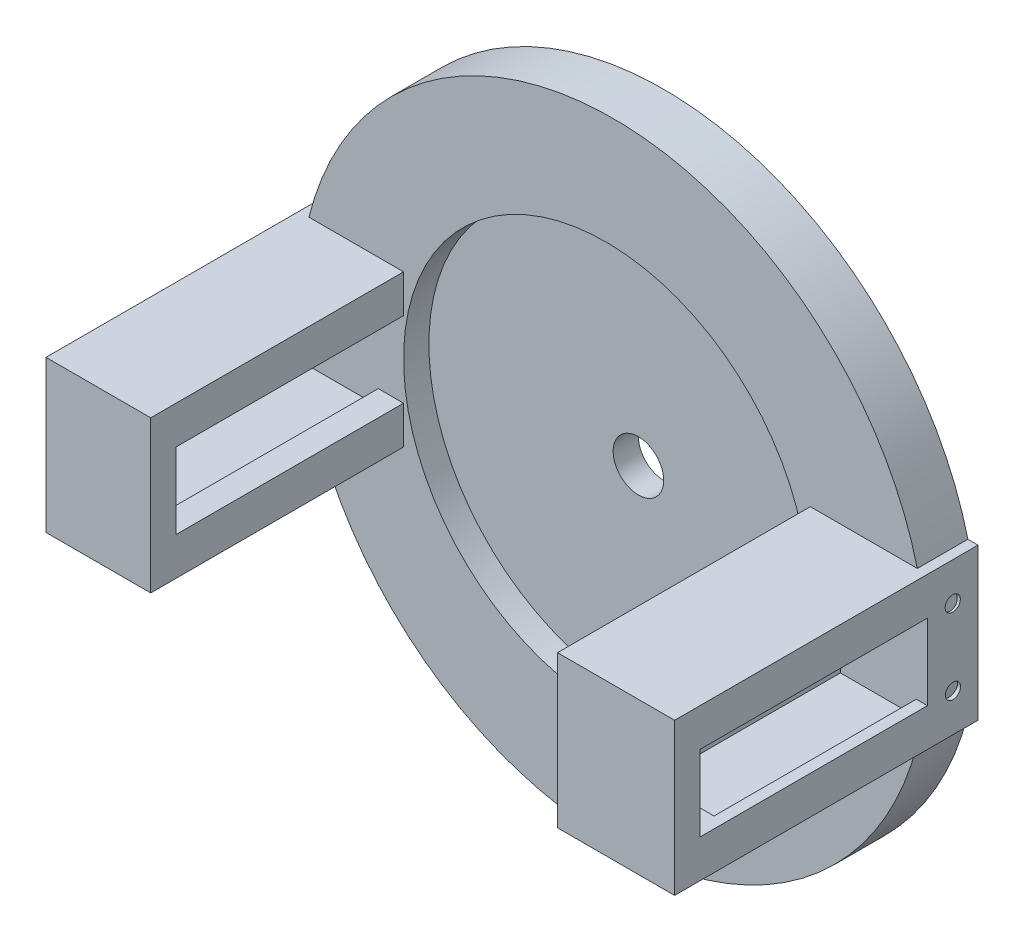
SolidWorks part; units mm, degrees
ref_plane "Ön Düzlem" through (0, 0, 0) normal (0, 0, 1) x (1, 0, 0)
ref_plane "Üst Düzlem" through (0, 0, 0) normal (0, 1, 0) x (1, 0, 0)
ref_plane "Sağ Düzlem" through (0, 0, 0) normal (1, 0, 0) x (0, 0, -1)
sketch "Çizim1" plane through (0, 0, 0) normal (0, 0, 1) x (1, 0, 0)
  circle A0 centre (0, 0) radius 62
  dimension "D1" = 124
extrude "Yükseklik-Ekstrüzyon1" add sketch "Çizim1" along normal blind 10
ref_plane "Düzlem1" through (64, 0, 0) normal (1, 0, 0) x (0, 0, -1)
sketch "Çizim2" plane through (64, 0, 0) normal (1, 0, 0) x (0, 0, -1)
  line L0 (0, -62) -> (0, 62) construction
  line L1 (0, 15) -> (-60, 15)
  line L2 (0, 15) -> (0, -15)
  line L3 (0, -15) -> (-60, -15)
  line L4 (-60, 15) -> (-60, -15)
  line L7 (-10, 7.5) -> (-55, 7.5)
  line L8 (-10, 7.5) -> (-10, -7.5)
  line L9 (-10, -7.5) -> (-55, -7.5)
  line L10 (-55, 7.5) -> (-55, -7.5)
  circle A0 centre (-5, 7.5) radius 1.5
  circle A1 centre (-4.9504, -7.5) radius 1.5
  dimension "D9" = 3
  dimension "D10" = 3
  dimension "D1" = 30
  dimension "D2" = 15
  dimension "D3" = 60
  dimension "D4" = 10
  dimension "D5" = 7.5
  dimension "D6" = 7.5
  dimension "D7" = 15
  dimension "D8" = 45
  dimension "D11" = 7.5
  dimension "D12" = 7.5
  dimension "D13" = 5
extrude "Yükseklik-Ekstrüzyon2" add sketch "Çizim2" against normal blind 25
pattern_circular "Dairesel Kaplama1" count 2 over 180 about axis through (-1.2231, 0, 0) along (0, 0, 1) of "Yükseklik-Ekstrüzyon2"
sketch "Çizim4" plane through (0, 7.5, 0) normal (0, -1, 0) x (1, 0, 0)
  line L0 (-60.1581, 10) -> (-41.4462, 10) construction
  line L1 (-46.4462, 10) -> (-61.4462, 10)
  line L2 (-46.4462, 10) -> (-46.4462, 50)
  line L3 (-46.4462, 50) -> (-61.4462, 50)
  line L4 (-61.4462, 10) -> (-61.4462, 50)
  line L5 (-66.4462, 0) -> (-66.4462, 60) construction
  line L6 (-41.4462, 10) -> (-41.4462, 60) construction
  line L7 (-41.4462, 60) -> (-66.4462, 60) construction
  dimension "D1" = 15
  dimension "D2" = 5
  dimension "D3" = 5
  dimension "D4" = 10
  dimension "D5" = 40
extrude "Kes-Ekstrüzyon1" cut sketch "Çizim4" against normal blind 3 and the other way blind 18
pattern_circular "Dairesel Kaplama2" count 2 every 180 about axis through (-0.7491, 0, 0) along (0, 0, 1) of "Kes-Ekstrüzyon1"
sketch "Çizim5" plane through (0, 0, 10) normal (0, 0, 1) x (1, 0, 0)
  circle A0 centre (-1.4435, 0.1372) radius 40
  dimension "D1" = 80
sketch "Çizim6" plane through (0, 0, 0) normal (0, 1, 0) x (1, 0, 0)
  line L0 (-60.1581, 0) -> (-60.1581, -10) construction
  line L3 (-41.4462, -60) -> (-66.4462, -60) construction
  line L4 (-66.4462, 0) -> (-62.1581, 0)
  line L5 (-66.4462, 0) -> (-66.4462, -60)
  line L6 (-66.4462, -60) -> (-62.1581, -60)
  line L7 (-62.1581, 0) -> (-62.1581, -60)
  line L8 (39, -60) -> (64, -60) construction
  line L9 (64, 0) -> (62.1581, 0)
  line L10 (64, 0) -> (64, -60)
  line L11 (64, -60) -> (62.1581, -60)
  line L12 (62.1581, 0) -> (62.1581, -60)
  line L13 (60.1581, -10) -> (60.1581, 0) construction
  dimension "D1" = 2
  dimension "D2" = 2
extrude "Kes-Ekstrüzyon3" cut sketch "Çizim6" against normal mid plane 40
extrude "Kes-Ekstrüzyon4" cut sketch "Çizim5" against normal blind 5
ref_plane "Düzlem2" through (-41.4462, 7.5, 10) normal (-1, 0, 0) x (0, 0, 1)
sketch "Çizim7" plane through (0, 0, 0) normal (0, 0, -1) x (-1, 0, 0)
  circle A0 centre (0, 0) radius 5
  dimension "D1" = 10
extrude "Kes-Ekstrüzyon5" cut sketch "Çizim7" against normal blind 10
